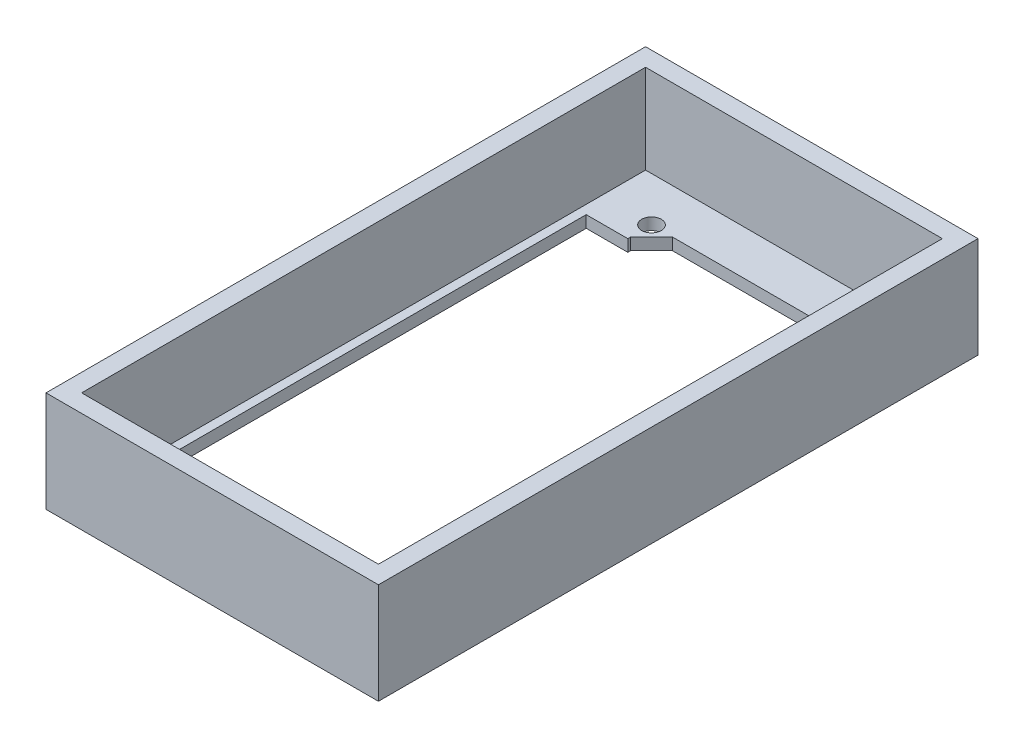
SolidWorks part; units mm, degrees
ref_plane "Front Plane" through (0, 0, 0) normal (0, 0, 1) x (1, 0, 0)
ref_plane "Top Plane" through (0, 0, 0) normal (0, 1, 0) x (1, 0, 0)
ref_plane "Right Plane" through (0, 0, 0) normal (1, 0, 0) x (0, 0, -1)
sketch "Sketch1" plane through (0, 0, 0) normal (0, 1, 0) x (1, 0, 0)
  line L0 (0, 71.821) -> (0, -60.7952) construction
  line L1 (-147.0111, 0) -> (122.0111, 0) construction
  line L3 (-13.5, 41.5) -> (13.5, 41.5) construction
  line L4 (-13.5, 41.5) -> (-13.5, -41.5) construction
  line L5 (-13.5, -41.5) -> (13.5, -41.5) construction
  line L6 (13.5, 41.5) -> (13.5, -41.5) construction
  line L7 (28, 50.5) -> (28, -50.5)
  line L9 (-28, 50.5) -> (-28, -50.5)
  line L10 (16.5, 44.5) -> (16.5, 37.5) construction
  line L11 (-16.5, -44.5) -> (16.5, -44.5) construction
  line L12 (-16.5, 44.5) -> (-16.5, 37.5) construction
  line L13 (-16.5, 44.5) -> (16.5, 44.5) construction
  line L14 (-28, 56) -> (28, 56) construction
  line L15 (-28, 50.5) -> (28, 50.5)
  line L16 (-28, 56) -> (-28, -56) construction
  line L17 (28, 56) -> (28, -56) construction
  line L18 (-28, -56) -> (28, -56) construction
  line L19 (-28, -50.5) -> (28, -50.5)
  line L20 (-12.9645, -40) -> (12.9645, -40)
  line L21 (16.5, 36.4645) -> (16.5, -36.4645)
  line L22 (-12.9645, 40) -> (12.9645, 40)
  line L23 (-16.5, 36.4645) -> (-16.5, -36.4645)
  line L24 (-16.5, 36.4645) -> (-12.9645, 40)
  line L25 (-16.5, 36.4645) -> (-16.5, -36.4645) construction
  line L26 (-16.5, 44.5) -> (-16.5, -44.5) construction
  line L27 (16.5, 36.4645) -> (12.9645, 40)
  line L28 (16.5, 36.4645) -> (16.5, -36.4645) construction
  line L29 (16.5, 44.5) -> (16.5, -44.5) construction
  line L30 (-12.9645, -40) -> (-16.5, -36.4645)
  line L31 (-16.5, -37.5) -> (-16.5, -44.5) construction
  line L32 (12.9645, -40) -> (16.5, -36.4645)
  line L33 (16.5, -37.5) -> (16.5, -44.5) construction
  circle A8 centre (-16.5, 40) radius 1.5 construction
  circle A9 centre (16.5, 40) radius 1.5 construction
  circle A10 centre (-16.5, 40) radius 1.65
  circle A11 centre (16.5, 40) radius 1.65
  circle A12 centre (-16.5, -40) radius 1.5 construction
  circle A13 centre (16.5, -40) radius 1.5 construction
  circle A14 centre (-16.5, -40) radius 1.65
  circle A15 centre (16.5, -40) radius 1.65
  arc A16 (-16.5, 37.5) -> (-14, 40) centre (-16.5, 40) ccw construction
  arc A17 (14, 40) -> (16.5, 37.5) centre (16.5, 40) ccw construction
  arc A18 (16.5, -37.5) -> (14, -40) centre (16.5, -40) ccw construction
  arc A19 (-14, -40) -> (-16.5, -37.5) centre (-16.5, -40) ccw construction
  point P9 (0, 41.5)
  point P10 (-13.5, 0)
  dimension "D5" = 3
  dimension "D6" = 3
  dimension "D7" = 3.3
  dimension "D8" = 3.3
  dimension "D11" = 3
  dimension "D12" = 3
  dimension "D13" = 3.3
  dimension "D14" = 3.3
  dimension "D15" = 80
  dimension "D2" = 33
  dimension "D16" = 5
  dimension "D17" = 5
  dimension "D18" = 5
  dimension "D19" = 5
  dimension "D9" = 9
  dimension "D10" = 9
  dimension "D3" = 14.5
  dimension "D4" = 3
extrude "Boss-Extrude1" add sketch "Sketch1" along normal blind 2
sketch "Sketch3" plane through (0, 2, 0) normal (0, 1, 0) x (1, 0, 0)
  line L0 (-28, 50.5) -> (-28, -50.5) construction
  line L1 (28, 50.5) -> (-28, 50.5) construction
  line L2 (28, -50.5) -> (28, 50.5) construction
  line L3 (-28, -50.5) -> (28, -50.5) construction
  line L4 (-28, 50.5) -> (-28, -50.5)
  line L5 (28, 50.5) -> (-28, 50.5)
  line L6 (28, -50.5) -> (28, 50.5)
  line L7 (-28, -50.5) -> (28, -50.5)
  line L8 (-25, 47.5) -> (-25, -47.5)
  line L9 (-25, -47.5) -> (25, -47.5)
  line L10 (25, -47.5) -> (25, 47.5)
  line L11 (25, 47.5) -> (-25, 47.5)
  dimension "D1" = 3
extrude "Boss-Extrude2" add sketch "Sketch3" along normal blind 15
sketch "Sketch5" plane through (0, 2, 0) normal (0, 1, 0) x (1, 0, 0)
  line L0 (-41.4369, 0) -> (47.6962, 0) construction
  line L1 (-16.5, 36) -> (-16.5, -36)
  line L2 (-16.5, 36.4645) -> (-16.5, -36.4645) construction
  line L3 (-16.5, 36) -> (-23.5, 36)
  line L4 (-23.5, 36) -> (-23.5, -36)
  line L5 (-23.5, -36) -> (-16.5, -36)
  point P7 (-16.5, 0)
  dimension "D1" = 72
  dimension "D2" = 7
extrude "Cut-Extrude2" cut sketch "Sketch5" against normal through all
